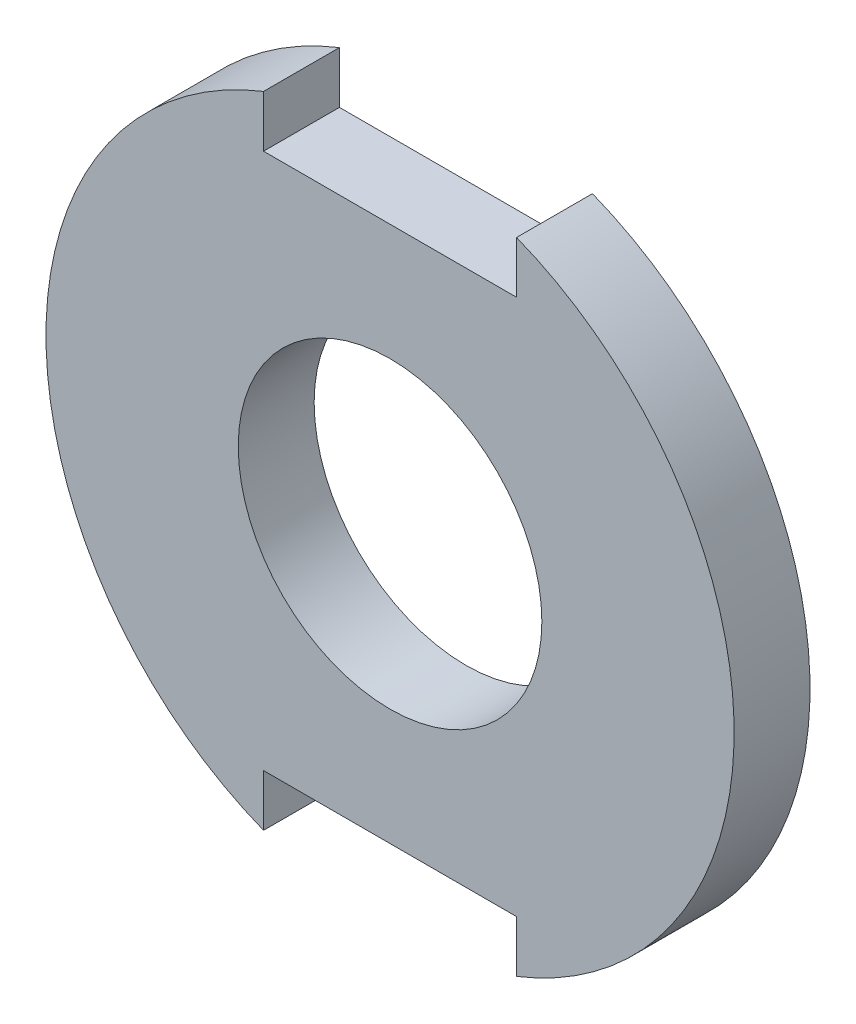
SolidWorks part; units mm, degrees
ref_plane "정면" through (0, 0, 0) normal (0, 0, 1) x (1, 0, 0)
ref_plane "윗면" through (0, 0, 0) normal (0, 1, 0) x (1, 0, 0)
ref_plane "우측면" through (0, 0, 0) normal (1, 0, 0) x (0, 0, -1)
sketch "스케치1" plane through (0, 0, 0) normal (0, 0, 1) x (1, 0, 0)
  circle A0 centre (0, 0) radius 13.6
  circle A1 centre (0, 0) radius 6
  dimension "D1" = 27.2
  dimension "D2" = 12
extrude "보스-돌출1" add sketch "스케치1" along normal blind 3
sketch "스케치2" plane through (0, 0, 0) normal (0, 0, -1) x (-1, 0, 0)
  line L1 (-5, -10.6) -> (5, -10.6)
  line L2 (-5, -10.6) -> (-5, -16.6)
  line L3 (-5, -16.6) -> (5, -16.6)
  line L4 (5, -10.6) -> (5, -16.6)
  line L5 (-5, -10.6) -> (5, -16.6) construction
  line L6 (-5, -16.6) -> (5, -10.6) construction
  line L7 (-5, 16.6) -> (5, 16.6)
  line L8 (-5, 16.6) -> (-5, 10.6)
  line L9 (-5, 10.6) -> (5, 10.6)
  line L10 (5, 16.6) -> (5, 10.6)
  line L11 (-5, 16.6) -> (5, 10.6) construction
  line L12 (-5, 10.6) -> (5, 16.6) construction
  circle A0 centre (0, 0) radius 13.6 construction
  point P0 (0, -13.6)
  point P5 (0, 13.6)
  point P10 (0, 0)
  point P12 (0, 13.6)
  point P15 (0, -13.6)
  dimension "D1" = 10
  dimension "D2" = 10
  dimension "D3" = 3
  dimension "D4" = 3
extrude "컷-돌출1" cut sketch "스케치2" against normal blind 3
